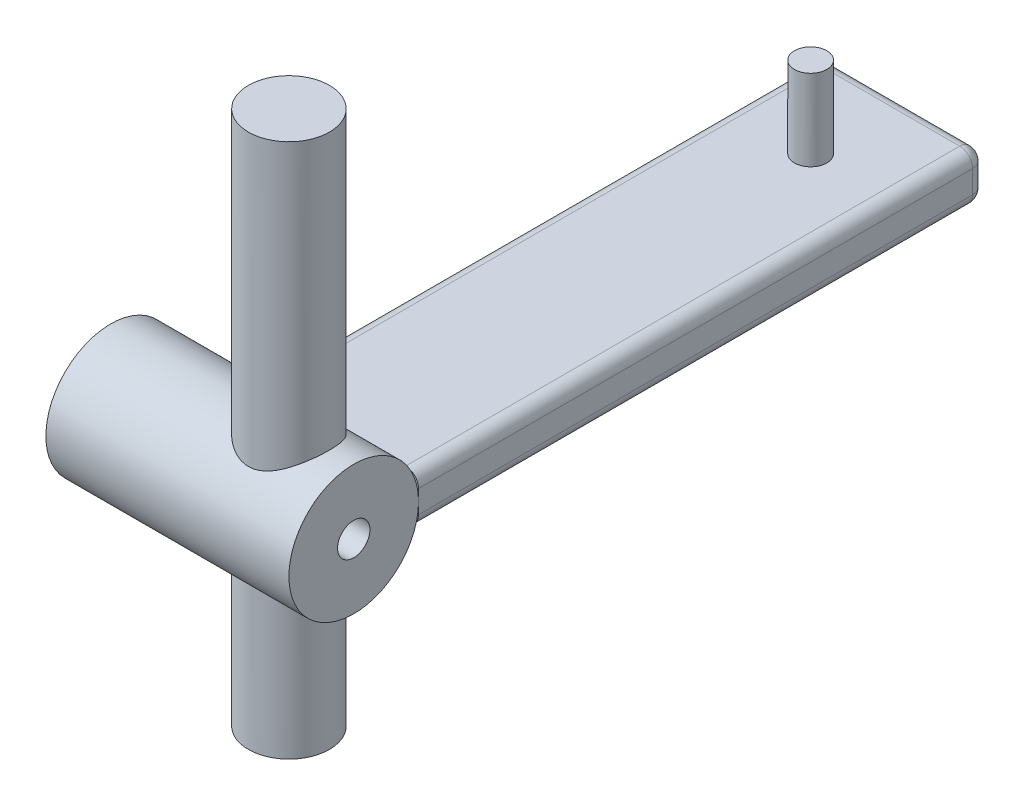
SolidWorks part; units mm, degrees
ref_plane "Front Plane" through (0, 0, 0) normal (0, 0, 1) x (1, 0, 0)
ref_plane "Top Plane" through (0, 0, 0) normal (0, 1, 0) x (1, 0, 0)
ref_plane "Right Plane" through (0, 0, 0) normal (1, 0, 0) x (0, 0, -1)
sketch "Sketch2" plane through (0, 0, 0) normal (1, 0, 0) x (0, 0, -1)
  circle A0 centre (0, 0) radius 4
  circle A1 centre (0, 0) radius 1
  dimension "D1" = 8
  dimension "D2" = 2
extrude "Boss-Extrude1" add sketch "Sketch2" along normal blind 15
sketch "Sketch3" plane through (15, 0, 0) normal (1, 0, 0) x (0, 0, -1)
  line L0 (0, 4) -> (0, -4) construction
  circle A0 centre (0, 0) radius 4 construction
ref_plane "Plane1" through (15, 4, 0) normal (0, 1, 0) x (1, 0, 0)
sketch "Sketch4" plane through (15, 4, 0) normal (0, 1, 0) x (1, 0, 0)
  line L0 (0, 4) -> (0, -4) construction
  line L1 (0, 0) -> (-4, 0) construction
  circle A0 centre (-4, 0) radius 2.5
  dimension "D2" = 5
  dimension "D1" = 4
extrude "Boss-Extrude2" add sketch "Sketch4" along normal blind 17 separate body
sketch "Sketch6" plane through (0, 4, 0) normal (0, -1, 0) x (1, 0, 0)
  circle A2 centre (11, 0) radius 2.5
  circle A3 centre (11, 0) radius 2.5
  dimension "D1" = 0
extrude "Boss-Extrude3" add sketch "Sketch6" along normal blind 16
sketch "Sketch8" plane through (15, 0, 0) normal (1, 0, 0) x (0, 0, -1)
  circle A2 centre (0, 0) radius 1
  circle A3 centre (0, 0) radius 1
  dimension "D1" = 0
extrude "Cut-Extrude1" cut sketch "Sketch8" against normal through all
sketch "Sketch9" plane through (15, 0, 0) normal (1, 0, 0) x (0, 0, -1)
  line L0 (-4, 0) -> (4, 0) construction
  circle A0 centre (0, 0) radius 4 construction
ref_plane "Plane3" through (15, 0, 4) normal (0, 0, 1) x (1, 0, 0)
sketch "Sketch10" plane through (15, 0, 4) normal (0, 0, 1) x (1, 0, 0)
  line L0 (0, 0) -> (-15, 0) construction
  line L1 (0, 4) -> (0, -4) construction
  line L2 (0, 1.5) -> (0, -1.5)
  line L3 (0, -1.5) -> (-10, -1.5)
  line L4 (-10, -1.5) -> (-10, 1.5)
  line L5 (-10, 1.5) -> (0, 1.5)
  line L6 (0, -1.5) -> (-10, 1.5) construction
  line L7 (-10, -1.5) -> (0, 1.5) construction
  point P9 (-5, 0)
  dimension "D1" = 3
  dimension "D2" = 10
ref_plane "Plane4" through (15, 0, -4) normal (0, 0, -1) x (-1, 0, 0)
sketch "Sketch12" plane through (15, 0, -4) normal (0, 0, -1) x (-1, 0, 0)
  line L4 (0, 1.5) -> (0, -1.5)
  line L5 (0, -1.5) -> (10, -1.5)
  line L6 (10, -1.5) -> (10, 1.5)
  line L7 (10, 1.5) -> (0, 1.5)
  line L8 (0, 1.5) -> (0, -1.5)
  line L9 (0, -1.5) -> (10, -1.5)
  line L10 (10, -1.5) -> (10, 1.5)
  line L11 (10, 1.5) -> (0, 1.5)
  dimension "D1" = 0
extrude "Boss-Extrude6" add sketch "Sketch12" along normal blind 35 separate body
fillet "Fillet2" radius 0.8 8 edges at (5, 0, -39) (10, -1.5, -39) (15, 0, -39) (10, 1.5, -39) (15, -1.5, -21.5) (15, 1.5, -21.5) (5, -1.5, -21.5) (5, 1.5, -21.5)
sketch "Sketch13" plane through (0, 1.5, 0) normal (0, 1, 0) x (1, 0, 0)
  line L0 (14.2, 38.2) -> (5.8, 38.2) construction
  circle A0 centre (10, 33.2) radius 1
  point P2 (0, 0)
  dimension "D1" = 2
  dimension "D2" = 5
extrude "Boss-Extrude7" add sketch "Sketch13" along normal blind 5
